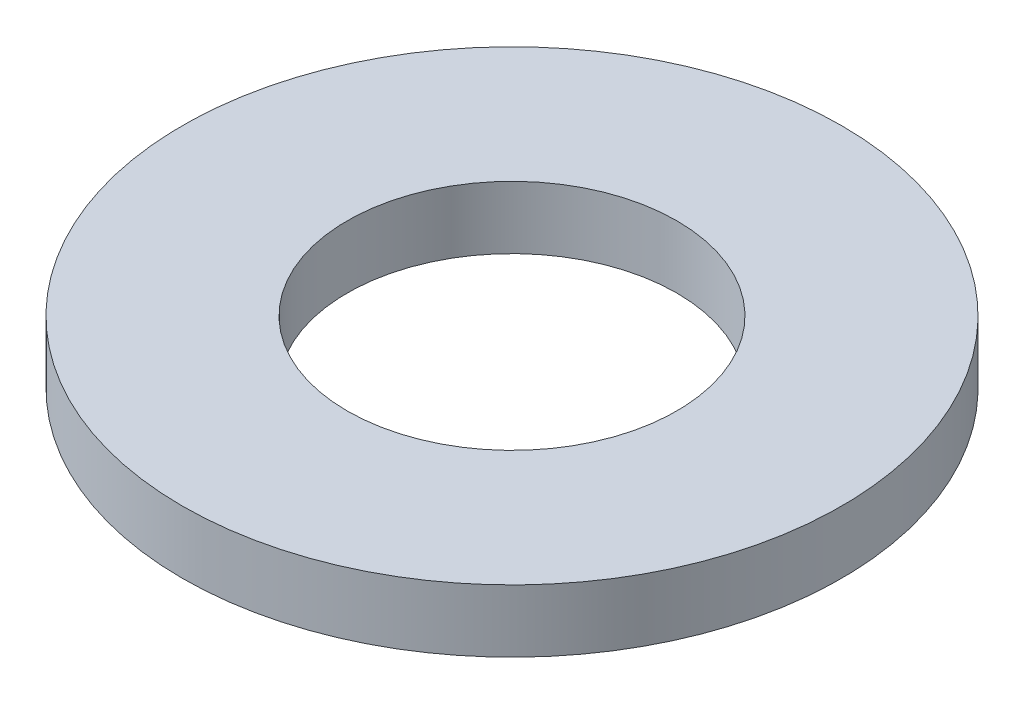
SolidWorks part; units mm, degrees
material "ABS"
ref_plane "Спереди" through (0, 0, 0) normal (0, 0, 1) x (1, 0, 0)
ref_plane "Сверху" through (0, 0, 0) normal (0, 1, 0) x (1, 0, 0)
ref_plane "Справа" through (0, 0, 0) normal (1, 0, 0) x (0, 0, -1)
sketch "Эскиз1" plane through (0, 0, 0) normal (0, 1, 0) x (1, 0, 0)
  circle A0 centre (0, 0) radius 6
  circle A1 centre (0, 0) radius 3
  dimension "D1" = 12
  dimension "D2" = 6
extrude "Бобышка-Вытянуть1" add sketch "Эскиз1" along normal blind 1.14
